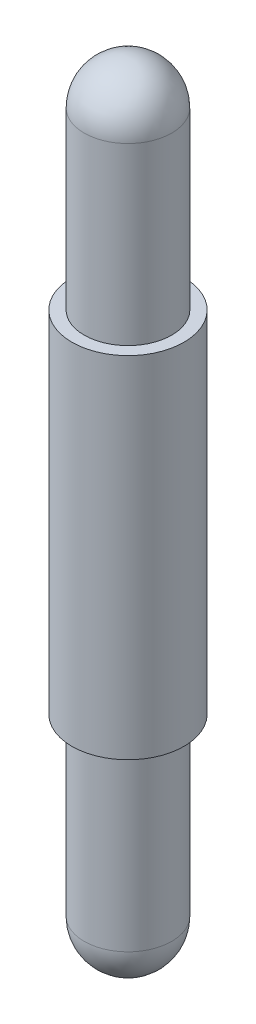
SolidWorks part; units mm, degrees
material "Plain Carbon Steel"
ref_plane "Front Plane" through (0, 0, 0) normal (0, 0, 1) x (1, 0, 0)
ref_plane "Top Plane" through (0, 0, 0) normal (0, 1, 0) x (1, 0, 0)
ref_plane "Right Plane" through (0, 0, 0) normal (1, 0, 0) x (0, 0, -1)
sketch "Sketch1" plane through (0, 0, 0) normal (0, 0, 1) x (1, 0, 0)
  line L0 (0, 118.9998) -> (0, -76.0082) construction
  line L1 (0, 73.9918) -> (12.5, 73.9918)
  line L2 (12.5, 73.9918) -> (12.5, 23.9918)
  line L3 (12.5, 23.9918) -> (16, 23.9918)
  line L4 (16, 23.9918) -> (16, -76.0082)
  line L5 (16, -76.0082) -> (12.5, -76.0082)
  line L6 (12.5, -76.0082) -> (12.5, -126.0082)
  line L7 (12.5, -126.0082) -> (0, -126.0082)
  line L8 (0, -76.0082) -> (0, -156.0614) construction
  line L9 (0, 86.4918) -> (0, -138.5082)
  arc A0 (12.5, 73.9918) -> (0, 86.4918) centre (0, 73.9918) ccw
  arc A1 (0, -138.5082) -> (12.5, -126.0082) centre (0, -126.0082) ccw
  dimension "D1" = 12.5
  dimension "D2" = 100
  dimension "D3" = 50
  dimension "D4" = 50
  dimension "D5" = 16
  dimension "D6" = 12.5
revolve "Revolve1" add sketch "Sketch1" angle 360 about L9
